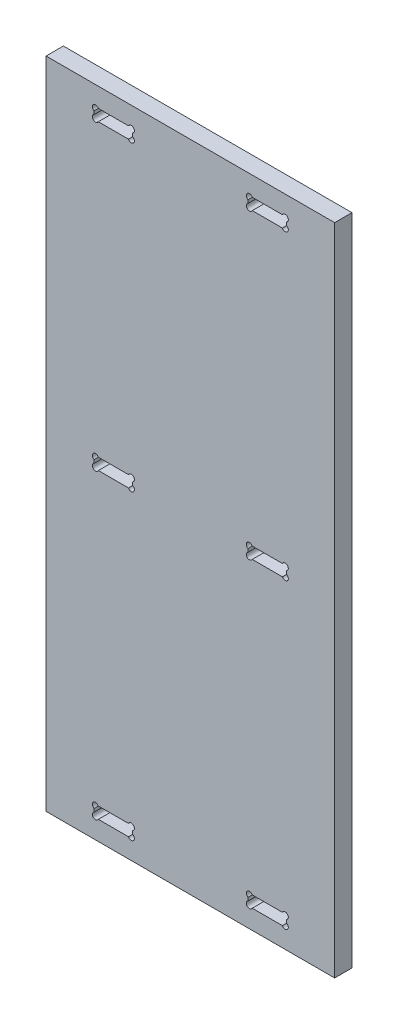
SolidWorks part; units mm, degrees
ref_plane "Front Plane" through (0, 0, 0) normal (0, 0, 1) x (1, 0, 0)
ref_plane "Top Plane" through (0, 0, 0) normal (0, 1, 0) x (1, 0, 0)
ref_plane "Right Plane" through (0, 0, 0) normal (1, 0, 0) x (0, 0, -1)
sketch "Sketch1" plane through (0, 0, 0) normal (0, 0, 1) x (1, 0, 0)
  line L0 (1280.0622, 3439.2418) -> (1280.0622, 3419.2418)
  line L1 (1280.0622, 3419.2418) -> (1280.0622, 3407.2418)
  line L2 (1280.0622, 3407.2418) -> (1280.0622, 3105.2418)
  line L3 (1280.0622, 3105.2418) -> (1280.0622, 3093.2418)
  line L4 (1525.7218, 3093.2418) -> (1494.4026, 3093.2418)
  line L5 (1365.7218, 2791.2418) -> (1334.4026, 2791.2418)
  line L6 (1365.7218, 2779.2418) -> (1334.4026, 2779.2418)
  line L7 (1280.0622, 3439.2418) -> (1580.0622, 3439.2418)
  line L8 (1330.0622, 3414.9014) -> (1330.0622, 3411.5822)
  line L9 (1370.0622, 3414.9014) -> (1370.0622, 3411.5822)
  line L10 (1370.0622, 2783.5822) -> (1370.0622, 2786.9014)
  line L11 (1365.7218, 3419.2418) -> (1334.4026, 3419.2418)
  line L12 (1365.7218, 3407.2418) -> (1334.4026, 3407.2418)
  line L13 (1330.0622, 2783.5822) -> (1330.0622, 2786.9014)
  line L14 (1280.0622, 2759.2418) -> (1580.0622, 2759.2418)
  line L15 (1280.0622, 2791.2418) -> (1280.0622, 3093.2418)
  line L16 (1280.0622, 2779.2418) -> (1280.0622, 2791.2418)
  line L17 (1280.0622, 2759.2418) -> (1280.0622, 2779.2418)
  line L18 (1334.4026, 3105.2418) -> (1365.7218, 3105.2418)
  line L19 (1530.0622, 3097.5822) -> (1530.0622, 3100.9014)
  line L21 (1365.7218, 3093.2418) -> (1334.4026, 3093.2418)
  line L22 (1370.0622, 3097.5822) -> (1370.0622, 3100.9014)
  line L23 (1330.0622, 3097.5822) -> (1330.0622, 3100.9014)
  line L25 (1490.0622, 3097.5822) -> (1490.0622, 3100.9014)
  line L27 (1494.4026, 3105.2418) -> (1525.7218, 3105.2418)
  line L29 (1580.0622, 2759.2418) -> (1580.0622, 2779.2418)
  line L30 (1580.0622, 2779.2418) -> (1580.0622, 2791.2418)
  line L31 (1580.0622, 2791.2418) -> (1580.0622, 3093.2418)
  line L32 (1530.0622, 2783.5822) -> (1530.0622, 2786.9014)
  line L33 (1494.4026, 3407.2418) -> (1525.7218, 3407.2418)
  line L34 (1494.4026, 3419.2418) -> (1525.7218, 3419.2418)
  line L35 (1490.0622, 2783.5822) -> (1490.0622, 2786.9014)
  line L36 (1490.0622, 3414.9014) -> (1490.0622, 3411.5822)
  line L37 (1530.0622, 3414.9014) -> (1530.0622, 3411.5822)
  line L38 (1494.4026, 2779.2418) -> (1525.7218, 2779.2418)
  line L39 (1494.4026, 2791.2418) -> (1525.7218, 2791.2418)
  line L40 (1580.0622, 3105.2418) -> (1580.0622, 3093.2418)
  line L41 (1580.0622, 3407.2418) -> (1580.0622, 3105.2418)
  line L42 (1580.0622, 3419.2418) -> (1580.0622, 3407.2418)
  line L43 (1580.0622, 3439.2418) -> (1580.0622, 3419.2418)
  arc A0 (1334.4026, 3419.2418) -> (1330.0622, 3414.9014) centre (1331.4764, 3417.8276) ccw
  arc A1 (1365.7218, 3419.2418) -> (1370.0622, 3414.9014) centre (1368.648, 3417.8276) cw
  arc A2 (1365.7218, 3407.2418) -> (1370.0622, 3411.5822) centre (1368.648, 3408.656) ccw
  arc A3 (1334.4026, 3407.2418) -> (1330.0622, 3411.5822) centre (1331.4764, 3408.656) cw
  arc A4 (1334.4026, 2791.2418) -> (1330.0622, 2786.9014) centre (1331.4764, 2789.8276) ccw
  arc A5 (1365.7218, 2791.2418) -> (1370.0622, 2786.9014) centre (1368.648, 2789.8276) cw
  arc A6 (1365.7218, 2779.2418) -> (1370.0622, 2783.5822) centre (1368.648, 2780.656) ccw
  arc A7 (1334.4026, 2779.2418) -> (1330.0622, 2783.5822) centre (1331.4764, 2780.656) cw
  arc A8 (1334.4026, 3105.2418) -> (1330.0622, 3100.9014) centre (1331.4764, 3103.8276) ccw
  arc A9 (1365.7218, 3105.2418) -> (1370.0622, 3100.9014) centre (1368.648, 3103.8276) cw
  arc A10 (1365.7218, 3093.2418) -> (1370.0622, 3097.5822) centre (1368.648, 3094.656) ccw
  arc A11 (1334.4026, 3093.2418) -> (1330.0622, 3097.5822) centre (1331.4764, 3094.656) cw
  arc A12 (1525.7218, 3093.2418) -> (1530.0622, 3097.5822) centre (1528.648, 3094.656) ccw
  arc A13 (1494.4026, 3093.2418) -> (1490.0622, 3097.5822) centre (1491.4764, 3094.656) cw
  arc A14 (1494.4026, 3105.2418) -> (1490.0622, 3100.9014) centre (1491.4764, 3103.8276) ccw
  arc A15 (1525.7218, 3105.2418) -> (1530.0622, 3100.9014) centre (1528.648, 3103.8276) cw
  arc A16 (1525.7218, 2779.2418) -> (1530.0622, 2783.5822) centre (1528.648, 2780.656) ccw
  arc A17 (1494.4026, 2779.2418) -> (1490.0622, 2783.5822) centre (1491.4764, 2780.656) cw
  arc A18 (1494.4026, 2791.2418) -> (1490.0622, 2786.9014) centre (1491.4764, 2789.8276) ccw
  arc A19 (1525.7218, 2791.2418) -> (1530.0622, 2786.9014) centre (1528.648, 2789.8276) cw
  arc A20 (1525.7218, 3407.2418) -> (1530.0622, 3411.5822) centre (1528.648, 3408.656) ccw
  arc A21 (1494.4026, 3407.2418) -> (1490.0622, 3411.5822) centre (1491.4764, 3408.656) cw
  arc A22 (1494.4026, 3419.2418) -> (1490.0622, 3414.9014) centre (1491.4764, 3417.8276) ccw
  arc A23 (1525.7218, 3419.2418) -> (1530.0622, 3414.9014) centre (1528.648, 3417.8276) cw
  dimension "D1" = 20
  dimension "D2" = 12
  dimension "D3" = 302
  dimension "D4" = 12
  dimension "D5" = 20
  dimension "D6" = 302
  dimension "D8" = 3.3192
sketch "Sketch2" plane through (0, 0, 0) normal (0, 0, 1) x (1, 0, 0)
  line L0 (1280.0622, 3439.2418) -> (1280.0622, 3419.2418)
  line L1 (1280.0622, 3419.2418) -> (1280.0622, 3407.2418)
  line L2 (1280.0622, 3407.2418) -> (1280.0622, 3105.2418)
  line L3 (1280.0622, 3105.2418) -> (1280.0622, 3093.2418)
  line L4 (1525.7218, 3093.2418) -> (1494.4026, 3093.2418)
  line L5 (1365.7218, 2791.2418) -> (1334.4026, 2791.2418)
  line L6 (1365.7218, 2779.2418) -> (1334.4026, 2779.2418)
  line L7 (1280.0622, 3439.2418) -> (1580.0622, 3439.2418)
  line L8 (1330.0622, 3414.9014) -> (1330.0622, 3411.5822)
  line L9 (1370.0622, 3414.9014) -> (1370.0622, 3411.5822)
  line L10 (1370.0622, 2783.5822) -> (1370.0622, 2786.9014)
  line L11 (1365.7218, 3419.2418) -> (1334.4026, 3419.2418)
  line L12 (1365.7218, 3407.2418) -> (1334.4026, 3407.2418)
  line L13 (1330.0622, 2783.5822) -> (1330.0622, 2786.9014)
  line L14 (1280.0622, 2759.2418) -> (1580.0622, 2759.2418)
  line L15 (1280.0622, 2791.2418) -> (1280.0622, 3093.2418)
  line L16 (1280.0622, 2779.2418) -> (1280.0622, 2791.2418)
  line L17 (1280.0622, 2759.2418) -> (1280.0622, 2779.2418)
  line L18 (1334.4026, 3105.2418) -> (1365.7218, 3105.2418)
  line L19 (1530.0622, 3097.5822) -> (1530.0622, 3100.9014)
  line L20 (1365.7218, 3105.2418) -> (1334.4026, 3105.2418)
  line L21 (1365.7218, 3093.2418) -> (1334.4026, 3093.2418)
  line L22 (1370.0622, 3097.5822) -> (1370.0622, 3100.9014)
  line L23 (1330.0622, 3097.5822) -> (1330.0622, 3100.9014)
  line L24 (1334.4026, 3093.2418) -> (1365.7218, 3093.2418)
  line L25 (1490.0622, 3097.5822) -> (1490.0622, 3100.9014)
  line L26 (1494.4026, 3093.2418) -> (1525.7218, 3093.2418)
  line L27 (1494.4026, 3105.2418) -> (1525.7218, 3105.2418)
  line L28 (1525.7218, 3105.2418) -> (1494.4026, 3105.2418)
  line L29 (1580.0622, 2759.2418) -> (1580.0622, 2779.2418)
  line L30 (1580.0622, 2779.2418) -> (1580.0622, 2791.2418)
  line L31 (1580.0622, 2791.2418) -> (1580.0622, 3093.2418)
  line L32 (1530.0622, 2783.5822) -> (1530.0622, 2786.9014)
  line L33 (1494.4026, 3407.2418) -> (1525.7218, 3407.2418)
  line L34 (1494.4026, 3419.2418) -> (1525.7218, 3419.2418)
  line L35 (1490.0622, 2783.5822) -> (1490.0622, 2786.9014)
  line L36 (1490.0622, 3414.9014) -> (1490.0622, 3411.5822)
  line L37 (1530.0622, 3414.9014) -> (1530.0622, 3411.5822)
  line L38 (1494.4026, 2779.2418) -> (1525.7218, 2779.2418)
  line L39 (1494.4026, 2791.2418) -> (1525.7218, 2791.2418)
  line L40 (1580.0622, 3105.2418) -> (1580.0622, 3093.2418)
  line L41 (1580.0622, 3407.2418) -> (1580.0622, 3105.2418)
  line L42 (1580.0622, 3419.2418) -> (1580.0622, 3407.2418)
  line L43 (1580.0622, 3439.2418) -> (1580.0622, 3419.2418)
  arc A0 (1334.4026, 3419.2418) -> (1330.0622, 3414.9014) centre (1331.4764, 3417.8276) ccw
  arc A1 (1365.7218, 3419.2418) -> (1370.0622, 3414.9014) centre (1368.648, 3417.8276) cw
  arc A2 (1365.7218, 3407.2418) -> (1370.0622, 3411.5822) centre (1368.648, 3408.656) ccw
  arc A3 (1334.4026, 3407.2418) -> (1330.0622, 3411.5822) centre (1331.4764, 3408.656) cw
  arc A4 (1334.4026, 2791.2418) -> (1330.0622, 2786.9014) centre (1331.4764, 2789.8276) ccw
  arc A5 (1365.7218, 2791.2418) -> (1370.0622, 2786.9014) centre (1368.648, 2789.8276) cw
  arc A6 (1365.7218, 2779.2418) -> (1370.0622, 2783.5822) centre (1368.648, 2780.656) ccw
  arc A7 (1334.4026, 2779.2418) -> (1330.0622, 2783.5822) centre (1331.4764, 2780.656) cw
  arc A8 (1334.4026, 3105.2418) -> (1330.0622, 3100.9014) centre (1331.4764, 3103.8276) ccw
  arc A9 (1365.7218, 3105.2418) -> (1370.0622, 3100.9014) centre (1368.648, 3103.8276) cw
  arc A10 (1365.7218, 3093.2418) -> (1370.0622, 3097.5822) centre (1368.648, 3094.656) ccw
  arc A11 (1334.4026, 3093.2418) -> (1330.0622, 3097.5822) centre (1331.4764, 3094.656) cw
  arc A12 (1525.7218, 3093.2418) -> (1530.0622, 3097.5822) centre (1528.648, 3094.656) ccw
  arc A13 (1494.4026, 3093.2418) -> (1490.0622, 3097.5822) centre (1491.4764, 3094.656) cw
  arc A14 (1494.4026, 3105.2418) -> (1490.0622, 3100.9014) centre (1491.4764, 3103.8276) ccw
  arc A15 (1525.7218, 3105.2418) -> (1530.0622, 3100.9014) centre (1528.648, 3103.8276) cw
  arc A16 (1525.7218, 2779.2418) -> (1530.0622, 2783.5822) centre (1528.648, 2780.656) ccw
  arc A17 (1494.4026, 2779.2418) -> (1490.0622, 2783.5822) centre (1491.4764, 2780.656) cw
  arc A18 (1494.4026, 2791.2418) -> (1490.0622, 2786.9014) centre (1491.4764, 2789.8276) ccw
  arc A19 (1525.7218, 2791.2418) -> (1530.0622, 2786.9014) centre (1528.648, 2789.8276) cw
  arc A20 (1525.7218, 3407.2418) -> (1530.0622, 3411.5822) centre (1528.648, 3408.656) ccw
  arc A21 (1494.4026, 3407.2418) -> (1490.0622, 3411.5822) centre (1491.4764, 3408.656) cw
  arc A22 (1494.4026, 3419.2418) -> (1490.0622, 3414.9014) centre (1491.4764, 3417.8276) ccw
  arc A23 (1525.7218, 3419.2418) -> (1530.0622, 3414.9014) centre (1528.648, 3417.8276) cw
  dimension "D1" = 20
  dimension "D2" = 12
  dimension "D3" = 302
  dimension "D4" = 12
  dimension "D5" = 20
  dimension "D6" = 302
  dimension "D8" = 3.3192
extrude "Boss-Extrude1" add sketch "Sketch1" along normal blind 18
